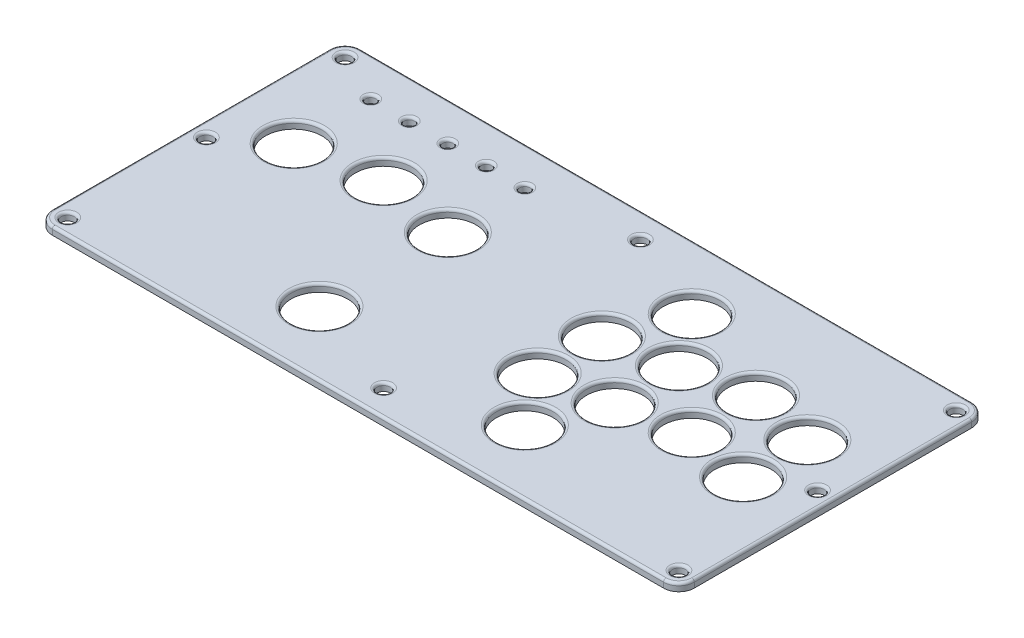
SolidWorks part; units mm, degrees
ref_plane "前视基准面" through (0, 0, 0) normal (0, 0, 1) x (1, 0, 0)
ref_plane "上视基准面" through (0, 0, 0) normal (0, 1, 0) x (1, 0, 0)
ref_plane "右视基准面" through (0, 0, 0) normal (1, 0, 0) x (0, 0, -1)
sketch "草图1" plane through (0, 0, 0) normal (0, 1, 0) x (1, 0, 0)
  line L0 (18.999, 127.3638) -> (256.999, 127.3638)
  line L1 (262.999, 121.3638) -> (262.999, 13.3638)
  line L2 (256.999, 7.3638) -> (18.999, 7.3638)
  line L3 (12.999, 13.3638) -> (12.999, 121.3638)
  arc A0 (18.999, 127.3638) -> (12.999, 121.3638) centre (18.999, 121.3638) ccw
  arc A1 (262.999, 121.3638) -> (256.999, 127.3638) centre (256.999, 121.3638) ccw
  arc A2 (256.999, 7.3638) -> (262.999, 13.3638) centre (256.999, 13.3638) ccw
  arc A3 (12.999, 13.3638) -> (18.999, 7.3638) centre (18.999, 13.3638) ccw
  circle A4 centre (18.999, 121.3638) radius 2.55
  circle A5 centre (256.999, 121.3638) radius 2.55
  circle A6 centre (137.999, 117.3638) radius 2.55
  circle A7 centre (18.999, 13.3638) radius 2.55
  circle A8 centre (256.999, 13.3638) radius 2.55
  circle A9 centre (137.999, 17.3638) radius 2.55
  circle A10 centre (256.999, 67.3638) radius 2.55
  circle A11 centre (18.999, 67.3638) radius 2.55
  circle A12 centre (162.999, 77.3638) radius 11
  circle A13 centre (187.999, 82.3638) radius 11
  circle A14 centre (212.999, 87.3638) radius 11
  circle A15 centre (237.999, 82.3638) radius 11
  circle A16 centre (162.999, 52.3638) radius 11
  circle A17 centre (187.999, 57.3638) radius 11
  circle A18 centre (212.999, 62.3638) radius 11
  circle A19 centre (237.999, 57.3638) radius 11
  circle A20 centre (172.999, 102.3638) radius 11
  circle A21 centre (177.999, 32.3638) radius 11
  circle A22 centre (97.999, 82.3638) radius 11
  circle A23 centre (67.999, 87.3638) radius 11
  circle A24 centre (37.999, 82.3638) radius 11
  circle A25 centre (97.999, 32.3638) radius 11
  circle B0 centre (37.999, 112.3638) radius 2
  circle B1 centre (52.999, 112.3638) radius 2
  circle B2 centre (67.999, 112.3638) radius 2
  circle B3 centre (82.999, 112.3638) radius 2
  circle B4 centre (97.999, 112.3638) radius 2
sketch_block_instance "*U1-1"
sketch_block "*U1"
extrude "凸台-拉伸1" add sketch "草图1" along normal blind 3
fillet "圆角1" radius 1 35 edges at (97.999, 3, -110.3638) (67.999, 3, -110.3638) (37.999, 3, -110.3638) (37.999, 3, -71.3638) (97.999, 3, -71.3638) (172.999, 3, -91.3638) (212.999, 3, -51.3638) (162.999, 3, -41.3638) (212.999, 3, -76.3638) (162.999, 3, -66.3638) (256.999, 3, -64.8138) (256.999, 3, -10.8138) (137.999, 3, -114.8138) (18.999, 3, -118.8138) (137.999, 3, -127.3638) (261.2416, 3, -125.6064) (262.999, 3, -67.3638) (261.2416, 3, -9.1212) (137.999, 3, -7.3638) (14.7564, 3, -9.1212) (12.999, 3, -67.3638) (14.7564, 3, -125.6064) (256.999, 3, -118.8138) (18.999, 3, -10.8138) (137.999, 3, -14.8138) (18.999, 3, -64.8138) (187.999, 3, -71.3638) (237.999, 3, -71.3638) (187.999, 3, -46.3638) (237.999, 3, -46.3638) (177.999, 3, -21.3638) (67.999, 3, -76.3638) (97.999, 3, -21.3638) (52.999, 3, -110.3638) (82.999, 3, -110.3638)
